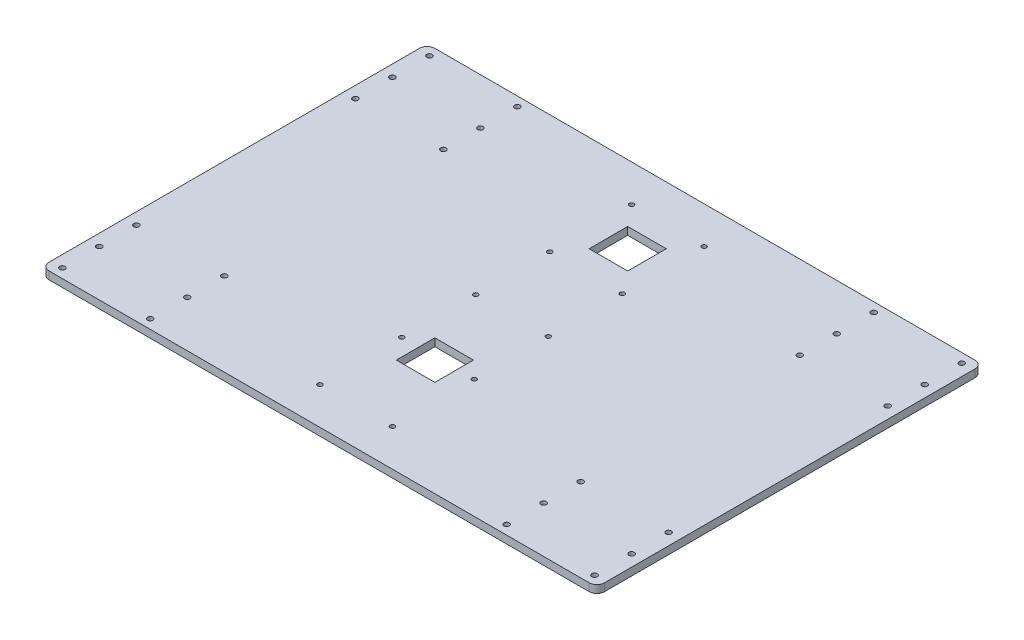
SolidWorks part; units mm, degrees
ref_plane "Front Plane" through (0, 0, 0) normal (0, 0, 1) x (1, 0, 0)
ref_plane "Top Plane" through (0, 0, 0) normal (0, 1, 0) x (1, 0, 0)
ref_plane "Right Plane" through (0, 0, 0) normal (1, 0, 0) x (0, 0, -1)
sketch "Sketch2" plane through (0, 0, 0) normal (0, 1, 0) x (1, 0, 0)
  line L0 (0, 125) -> (0, -125) construction
  line L1 (180, -125) -> (-180, -125)
  line L2 (180, -125) -> (180, 125)
  line L3 (180, 125) -> (-180, 125)
  line L4 (-180, -125) -> (-180, 125)
  line L5 (180, -125) -> (-180, 125) construction
  line L6 (180, 125) -> (-180, -125) construction
  line L7 (-172.5, 125) -> (-172.5, -125) construction
  line L8 (172.5, 125) -> (172.5, -125) construction
  line L9 (-144, 125) -> (-144, -125) construction
  line L10 (-180, 0) -> (180, 0) construction
  line L16 (-12.5, 87.5) -> (12.5, 87.5)
  line L17 (-12.5, 87.5) -> (-12.5, 62.5)
  line L18 (-12.5, 62.5) -> (12.5, 62.5)
  line L19 (12.5, 87.5) -> (12.5, 62.5)
  line L20 (-12.5, 87.5) -> (12.5, 62.5) construction
  line L21 (-12.5, 62.5) -> (12.5, 87.5) construction
  line L25 (-23.5, 125) -> (-23.5, -125) construction
  line L28 (-12.5, -62.5) -> (12.5, -62.5)
  line L29 (-12.5, -62.5) -> (-12.5, -37.5)
  line L30 (-12.5, -37.5) -> (12.5, -37.5)
  line L31 (12.5, -62.5) -> (12.5, -37.5)
  line L32 (-12.5, -62.5) -> (12.5, -37.5) construction
  line L33 (-12.5, -37.5) -> (12.5, -62.5) construction
  circle A0 centre (-172.5, 95) radius 1.75
  circle A1 centre (-172.5, 119) radius 1.75
  circle A2 centre (-172.5, 71) radius 1.75
  circle A3 centre (-115.5, 119) radius 1.75
  circle A4 centre (-115.5, 95) radius 1.75
  circle A5 centre (-115.5, 71) radius 1.75
  circle A6 centre (172.5, 71) radius 1.75
  circle A7 centre (172.5, 95) radius 1.75
  circle A8 centre (172.5, 119) radius 1.75
  circle A9 centre (115.5, 119) radius 1.75
  circle A10 centre (115.5, 95) radius 1.75
  circle A11 centre (115.5, 71) radius 1.75
  circle A12 centre (-172.5, -119) radius 1.75
  circle A13 centre (-172.5, -95) radius 1.75
  circle A14 centre (-172.5, -71) radius 1.75
  circle A15 centre (-115.5, -119) radius 1.75
  circle A16 centre (-115.5, -95) radius 1.75
  circle A17 centre (-115.5, -71) radius 1.75
  circle A18 centre (115.5, -71) radius 1.75
  circle A19 centre (115.5, -95) radius 1.75
  circle A20 centre (115.5, -119) radius 1.75
  circle A21 centre (172.5, -119) radius 1.75
  circle A22 centre (172.5, -95) radius 1.75
  circle A23 centre (172.5, -71) radius 1.75
  circle A34 centre (-23.5, 101) radius 1.5
  circle A35 centre (-23.5, -101) radius 1.5
  circle A36 centre (-23.5, 0) radius 1.5
  circle A37 centre (-23.5, 48) radius 1.5
  circle A38 centre (-23.5, -48) radius 1.5
  circle A39 centre (23.5, 101) radius 1.5
  circle A40 centre (23.5, 48) radius 1.5
  circle A41 centre (23.5, 0) radius 1.5
  circle A42 centre (23.5, -48) radius 1.5
  circle A43 centre (23.5, -101) radius 1.5
  point P0 (0, 0)
  point P64 (0, 0)
  point P65 (0, 75)
  point P70 (0, -50)
  dimension "D6" = 3.5
  dimension "D13" = 3
  dimension "D1" = 360
  dimension "D2" = 250
  dimension "D3" = 7.5
  dimension "D4" = 28.5
  dimension "D5" = 30
  dimension "D7" = 24
  dimension "D8" = 24
  dimension "D9" = 25
  dimension "D10" = 25
  dimension "D11" = 75
  dimension "D12" = 11
  dimension "D14" = 24
  dimension "D15" = 48
  dimension "D16" = 48
  dimension "D18" = 25
  dimension "D19" = 50
extrude "Boss-Extrude1" add sketch "Sketch2" along normal blind 5
fillet "Fillet1" radius 5 4 edges at (-180, 2.5, -125) (180, 2.5, -125) (180, 2.5, 125) (-180, 2.5, 125)
